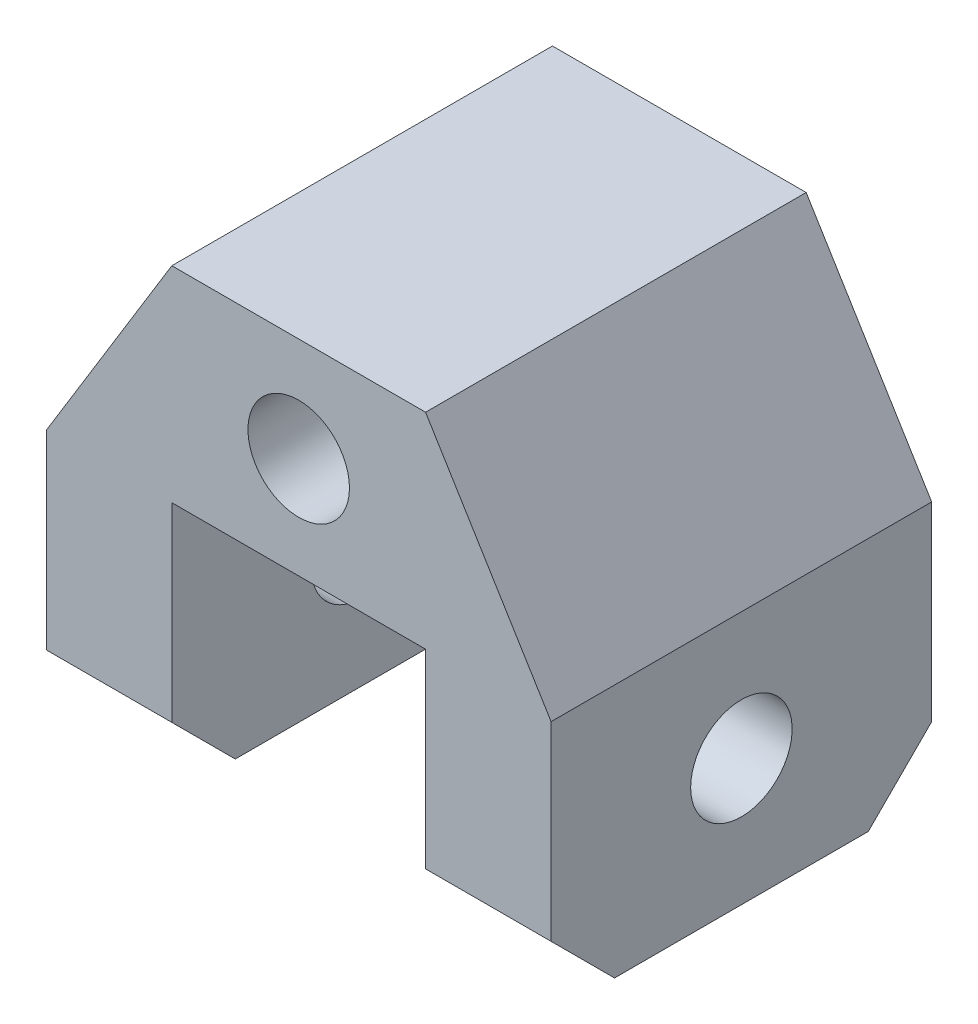
SolidWorks part; units mm, degrees
ref_plane "Спереди" through (0, 0, 0) normal (0, 0, 1) x (1, 0, 0)
ref_plane "Сверху" through (0, 0, 0) normal (0, 1, 0) x (1, 0, 0)
ref_plane "Справа" through (0, 0, 0) normal (1, 0, 0) x (0, 0, -1)
sketch "Эскиз1" plane through (0, 0, 0) normal (0, 0, 1) x (1, 0, 0)
  line L0 (25, 0) -> (25, 51.639) construction
  line L1 (15, 7.8964) -> (35, 7.8964)
  line L2 (5.1056, -8.2785) -> (5.1056, -28.2785)
  line L3 (5.1056, -28.2785) -> (15, -28.2785)
  line L4 (44.8944, -8.2785) -> (44.8944, -28.2785)
  line L5 (15, -28.2785) -> (15, -8.2785)
  line L6 (15, -8.2785) -> (35, -8.2785)
  line L7 (35, -28.2785) -> (35, -8.2785)
  line L8 (35, -28.2785) -> (44.8944, -28.2785)
  line L9 (35, 7.8964) -> (44.8944, -8.2785)
  line L13 (15, 7.8964) -> (5.1056, -8.2785)
  point P11 (25, -8.2785)
extrude "Вытянуть1" add sketch "Эскиз1" along normal blind 30
chamfer "Фаска1" distance 5 angle 45 4 edges at (10.0528, -28.2785, 0) (39.9472, -28.2785, 0) (39.9472, -28.2785, 30) (10.0528, -28.2785, 30)
sketch "Эскиз2" plane through (5.1056, 0, 0) normal (-1, 0, 0) x (0, 0, 1)
  line L0 (15, 9.373) -> (15, -10.3103) construction
  line L2 (25, -28.2785) -> (5, -28.2785) construction
  circle A0 centre (15, -18.2785) radius 4
  dimension "D1" = 10
extrude "Вытянуть2" cut sketch "Эскиз2" against normal through all
sketch "Эскиз3" plane through (0, 0, 30) normal (0, 0, 1) x (1, 0, 0)
  line L0 (25, 7.8964) -> (25, -12.6142) construction
  line L2 (15, -8.2785) -> (35, -8.2785) construction
  circle A0 centre (25, -0.2785) radius 4
  dimension "D1" = 8
extrude "Вытянуть3" cut sketch "Эскиз3" against normal through all
